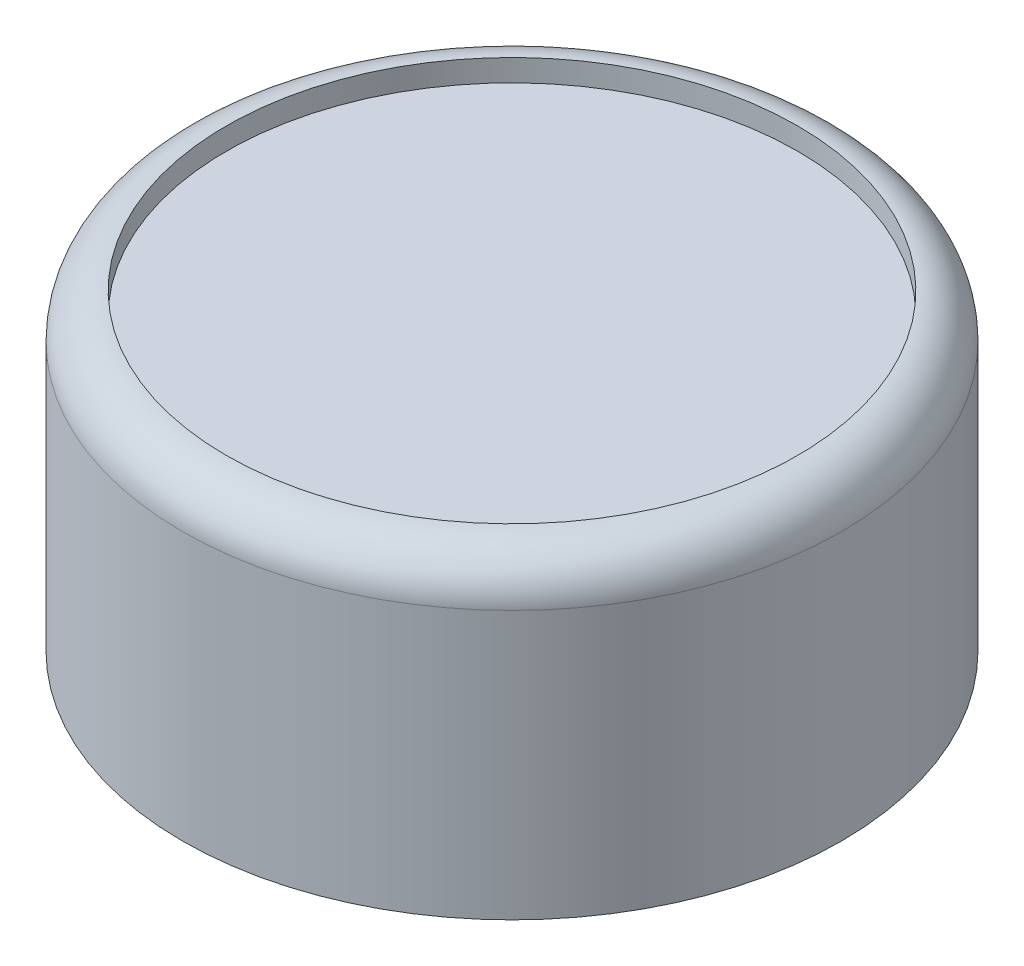
SolidWorks part; units mm, degrees
ref_plane "Front Plane" through (0, 0, 0) normal (0, 0, 1) x (1, 0, 0)
ref_plane "Top Plane" through (0, 0, 0) normal (0, 1, 0) x (1, 0, 0)
ref_plane "Right Plane" through (0, 0, 0) normal (1, 0, 0) x (0, 0, -1)
sketch "Sketch1" plane through (0, 0, 0) normal (0, 1, 0) x (1, 0, 0)
  circle A0 centre (0, 0) radius 15
  dimension "D1" = 30
extrude "Boss-Extrude1" add sketch "Sketch1" against normal blind 14.2 contours A0
shell "Shell1" thickness 2
sketch "Sketch2" plane through (0, -2, 0) normal (0, -1, 0) x (1, 0, 0)
  line L0 (-2.9665, -1.2) -> (2.9665, -1.2)
  line L2 (0, 3.2) -> (7.6102, 3.2) construction
  arc A0 (2.9665, -1.2) -> (-2.9665, -1.2) centre (0, 0) ccw
  dimension "D1" = 6.4
  dimension "D2" = 4.4
extrude "Extrude-Thin2" add sketch "Sketch2" along normal blind 7 thin
sketch "Sketch3" plane through (0, -9, 0) normal (0, -1, 0) x (1, 0, 0)
  line L0 (0, -13) -> (0, -3.2)
  line L1 (-4.0988, -3.2) -> (4.0988, -3.2) construction
  circle A0 centre (0, 0) radius 13 construction
  circle A1 centre (0, 0) radius 13 construction
rib "Rib1" sketch "Sketch3" sketch "Sketch3" thickness 2 extrusion direction normal to sketch draft on no parameters "D1"=2
pattern_circular "CirPattern1" count 4 over 360 about axis through (0, 0, 0) along (0, 1, 0) of "Rib1"
fillet "Fillet1" radius 2 1 edges at (0, 0, 15)
sketch "Sketch4" plane through (0, 0, 0) normal (0, 1, 0) x (1, 0, 0)
  circle A0 centre (0, 0) radius 13
extrude "Cut-Extrude1" cut sketch "Sketch4" against normal blind 1
